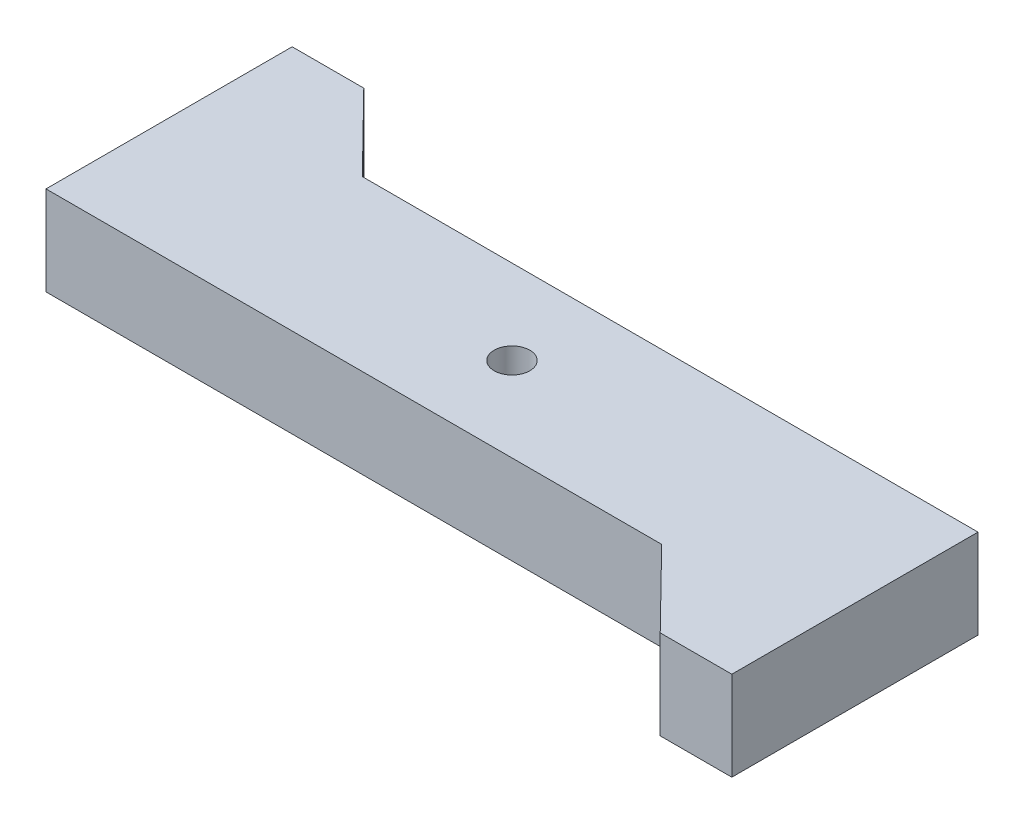
SolidWorks part; units mm, degrees
ref_plane "Front Plane" through (0, 0, 0) normal (0, 0, 1) x (1, 0, 0)
ref_plane "Top Plane" through (0, 0, 0) normal (0, 1, 0) x (1, 0, 0)
ref_plane "Right Plane" through (0, 0, 0) normal (1, 0, 0) x (0, 0, -1)
sketch "Sketch1" plane through (0, 0, 0) normal (0, 1, 0) x (1, 0, 0)
  line L0 (-85, -37.5) -> (85, 37.5) construction
  line L1 (-85.5361, 0) -> (85.5361, 0) construction
  line L2 (-85.5361, 18.9153) -> (-85.5361, -18.9153)
  line L3 (85.5361, 18.9153) -> (85.5361, -18.9153)
  line L4 (-52.4639, 18.9153) -> (85.5361, 18.9153)
  line L5 (-85.5361, -18.9153) -> (52.4639, -18.9153)
  line L6 (-85.5361, 18.9153) -> (-85.5361, 36.2605)
  line L7 (-85.5361, 36.2605) -> (-69.484, 36.2605)
  line L8 (-69.484, 36.2605) -> (-52.4639, 18.9153)
  line L9 (85.5361, -18.9153) -> (85.5361, -36.2605)
  line L10 (85.5361, -36.2605) -> (69.484, -36.2605)
  line L11 (69.484, -36.2605) -> (52.4639, -18.9153)
  point P2 (0, 0)
  point P10 (-85.5361, 0)
  point P11 (85.5361, 0)
  point P12 (50.8931, -18.9153)
  point P14 (0, 0)
  dimension "D1" = 75
  dimension "D2" = 170
extrude "Boss-Extrude1" add sketch "Sketch1" along normal blind 20
sketch "Sketch2" plane through (0, 20, 0) normal (0, 1, 0) x (1, 0, 0)
  circle A0 centre (0, 0) radius 4
extrude "Cut-Extrude1" cut sketch "Sketch2" against normal blind 20
